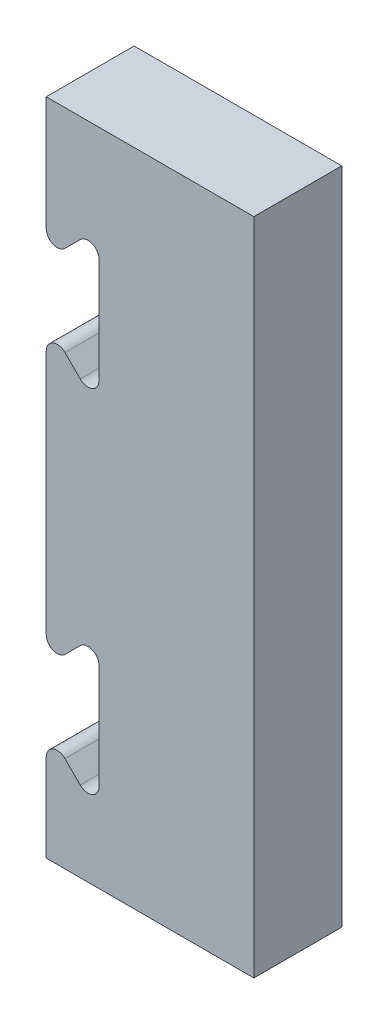
SolidWorks part; units mm, degrees
material "PET"
ref_plane "Front Plane" through (0, 0, 0) normal (0, 0, 1) x (1, 0, 0)
ref_plane "Top Plane" through (0, 0, 0) normal (0, 1, 0) x (1, 0, 0)
ref_plane "Right Plane" through (0, 0, 0) normal (1, 0, 0) x (0, 0, -1)
sketch "Sketch2" plane through (0, 0, 0) normal (0, 0, 1) x (1, 0, 0)
  line L0 (0, 0) -> (130, 0)
  line L1 (130, 0) -> (130, 14)
  line L2 (130, 14) -> (75, 69)
  line L3 (75, 69) -> (75, 120)
  line L4 (75, 120) -> (0, 120)
  line L5 (0, 120) -> (0, 0)
  dimension "D1" = 120
  dimension "D2" = 75
  dimension "D3" = 14
  dimension "D4" = 55
  dimension "D5" = 130
extrude "Boss-Extrude1" add sketch "Sketch2" against normal blind 10
sketch "Sketch3" plane through (0, 0, 0) normal (0, 0, 1) x (1, 0, 0)
  line L0 (75, 69) -> (75, 120) construction
  line L1 (0, 120) -> (75, 120)
  line L2 (0, 120) -> (0, 117)
  line L3 (0, 117) -> (75, 117)
  line L4 (75, 120) -> (75, 117)
  line L5 (0, 120) -> (75, 117) construction
  line L6 (0, 117) -> (75, 120) construction
  line L7 (0, 120) -> (0, 0) construction
  line L8 (0, 81) -> (75, 81)
  line L9 (0, 81) -> (0, 78)
  line L10 (0, 78) -> (75, 78)
  line L11 (75, 81) -> (75, 78)
  line L12 (0, 81) -> (75, 78) construction
  line L13 (0, 78) -> (75, 81) construction
  point P4 (37.5, 118.5)
  point P12 (37.5, 79.5)
  dimension "D1" = 3
  dimension "D2" = 36
extrude "Boss-Extrude2" add sketch "Sketch3" along normal blind 6.5
sketch "Sketch4" plane through (0, 0, 0) normal (0, 0, 1) x (1, 0, 0)
  line L0 (0, 99) -> (75, 99) construction
  line L1 (0, 117) -> (0, 81) construction
  line L2 (75, 81) -> (75, 117) construction
  circle A0 centre (10, 99) radius 3
  circle A1 centre (65, 99) radius 3
  dimension "D1" = 10
  dimension "D3" = 6
  dimension "D2" = 10
extrude "Cut-Extrude2" cut sketch "Sketch4" against normal up to surface (10 mm away) up to face at (68.3333, 53.8333, -10)
sketch "Sketch5" plane through (0, 0, 0) normal (0, 0, 1) x (1, 0, 0)
  line L0 (0, 0) -> (130, 0) construction
  line L1 (130, 14) -> (104, 14)
  line L2 (130, 14) -> (130, 0)
  line L3 (130, 0) -> (104, 0)
  line L4 (104, 14) -> (104, 0)
  line L5 (130, 14) -> (104, 0) construction
  line L6 (130, 0) -> (104, 14) construction
  line L7 (69, 0) -> (69, 120) construction
  line L8 (75, 120) -> (0, 120) construction
  line L9 (8, 0) -> (34, 0)
  line L10 (34, 14) -> (34, 0)
  line L11 (8, 14) -> (34, 14)
  line L12 (8, 14) -> (8, 0)
  line L13 (0, 78) -> (0, 0) construction
  point P4 (117, 7)
  dimension "D1" = 26
  dimension "D2" = 8
extrude "Boss-Extrude3" add sketch "Sketch5" along normal blind 60
sketch "Sketch6" plane through (0, 0, 0) normal (0, 0, 1) x (1, 0, 0)
  line L0 (0, 16) -> (6, 16) construction
  line L1 (0, 78) -> (0, 0) construction
  line L2 (0, 13) -> (6, 7)
  line L3 (6, 7) -> (6, 25)
  line L4 (6, 25) -> (0, 19)
  line L5 (8, 0) -> (34, 0) construction
  line L6 (0, 19) -> (0, 13)
  line L7 (0, 36) -> (-23.6105, 36) construction
  line L8 (0, 56) -> (6, 56) construction
  line L9 (6, 47) -> (0, 53)
  line L10 (6, 65) -> (6, 47)
  line L11 (0, 59) -> (6, 65)
  line L12 (0, 53) -> (0, 59)
  dimension "D1" = 6
  dimension "D2" = 6
  dimension "D3" = 16
  dimension "D4" = 6
  dimension "D5" = 40
sketch "Sketch7" plane through (0, 0, 0) normal (0, 0, 1) x (1, 0, 0)
  line L0 (60, 0) -> (60, 120) construction
  line L1 (34, 0) -> (104, 0) construction
  line L2 (75, 120) -> (0, 120) construction
  line L3 (60, 13) -> (60, 60) construction
  line L4 (53, 13) -> (53, 60)
  line L5 (67, 13) -> (67, 60)
  arc A0 (53, 13) -> (67, 13) centre (60, 13) ccw
  arc A1 (67, 60) -> (53, 60) centre (60, 60) ccw
  point P4 (60, 36.5)
  point P14 (60, 6)
  point P15 (60, 67)
  dimension "D1" = 26
  dimension "D2" = 7
  dimension "D3" = 6
extrude "Boss-Extrude5" add sketch "Sketch7" along normal blind 4
sketch "Sketch8" plane through (0, 0, 4) normal (0, 0, 1) x (1, 0, 0)
  line L4 (62.2, 13) -> (62.2, 60)
  line L5 (57.8, 60) -> (57.8, 13)
  line L6 (62.2, 13) -> (62.2, 60)
  line L7 (57.8, 60) -> (57.8, 13)
  arc A4 (57.8, 13) -> (62.2, 13) centre (60, 13) ccw
  arc A5 (62.2, 60) -> (57.8, 60) centre (60, 60) ccw
  arc A6 (57.8, 13) -> (62.2, 13) centre (60, 13) ccw
  arc A7 (62.2, 60) -> (57.8, 60) centre (60, 60) ccw
  dimension "D1" = 4.8
extrude "Cut-Extrude3" cut sketch "Sketch8" against normal through all
fillet "Fillet2" radius 3 4 edges at (75, 120, -1.75) (0, 120, -1.75) (37.5, 78, 0) (75, 69, -5)
extrude "Cut-Extrude4" cut sketch "Sketch6" against normal through all
fillet "Fillet3" radius 1.25 8 edges at (6, 25, -5) (6, 7, -5) (0, 13, -5) (0, 19, -5) (6, 47, -5) (0, 53, -5) (6, 65, -5) (0, 59, -5)
sketch "Sketch9" plane through (0, 0, 0) normal (0, 0, 1) x (1, 0, 0)
  line L0 (75, 75) -> (0, 75) construction
  line L1 (0, 0) -> (23.6144, 0)
  line L2 (0, 0) -> (0, 75)
  line L3 (0, 75) -> (23.6144, 75)
  line L4 (23.6144, 0) -> (23.6144, 75)
  line L5 (0, 0) -> (23.6144, 75) construction
  line L6 (0, 75) -> (23.6144, 0) construction
  point P4 (11.8072, 37.5)
extrude "Cut-Extrude6" cut sketch "Sketch9" against normal up to surface (10 mm away) flip side to cut up to face at (60, 36.5, -10)
sketch "Sketch10" plane through (0, 0, 60) normal (0, 0, 1) x (1, 0, 0)
  line L4 (8, 14) -> (8, 0)
  line L5 (8, 0) -> (34, 0)
  line L6 (34, 0) -> (34, 14)
  line L7 (34, 14) -> (8, 14)
  line L8 (8, 14) -> (8, 0)
  line L9 (8, 0) -> (34, 0)
  line L10 (34, 0) -> (34, 14)
  line L11 (34, 14) -> (8, 14)
  dimension "D1" = 0
extrude "Cut-Extrude7" cut sketch "Sketch10" against normal up to surface (60 mm away) up to face at (5.0559, 34.2727, 0)
